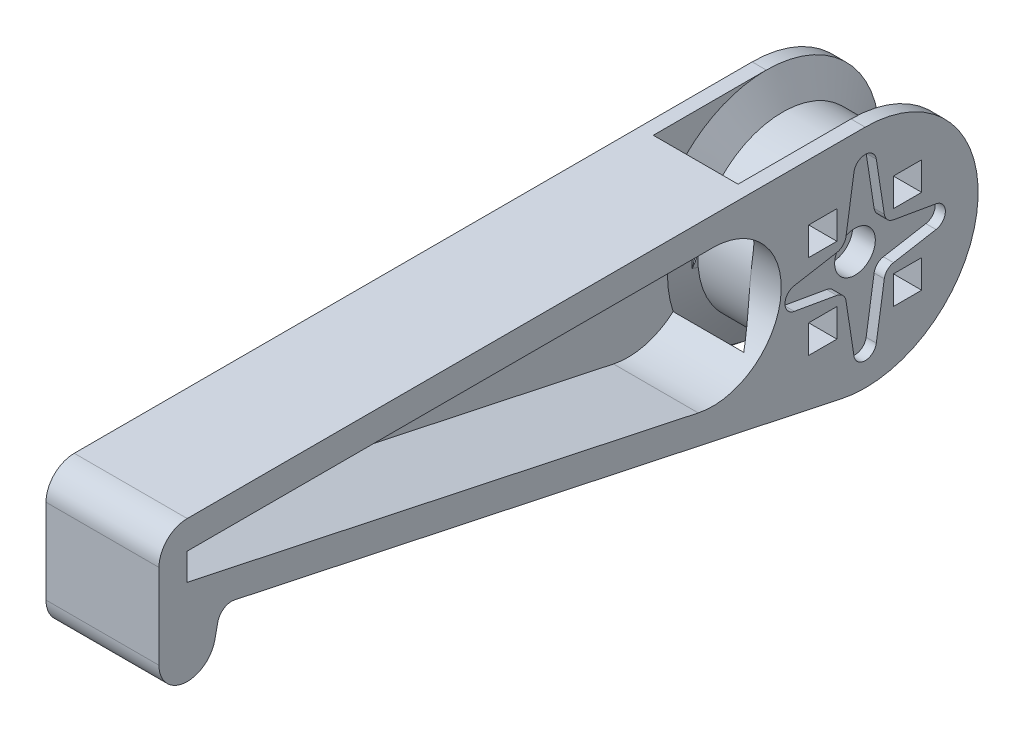
SolidWorks part; units mm, degrees
ref_plane "Front Plane" through (0, 0, 0) normal (0, 0, 1) x (1, 0, 0)
ref_plane "Top Plane" through (0, 0, 0) normal (0, 1, 0) x (1, 0, 0)
ref_plane "Right Plane" through (0, 0, 0) normal (1, 0, 0) x (0, 0, -1)
sketch "Sketch1" plane through (0, 0, 0) normal (1, 0, 0) x (0, 0, -1)
  line L0 (-141.7611, 4.2263) -> (-5.2917, -24.8427)
  line L1 (-146.1893, -1.3229) -> (-145.5279, 1.7824)
  line L2 (0, 25.4) -> (-152.4, 25.4)
  line L3 (-158.75, 19.05) -> (-158.75, 0)
  arc A0 (-5.2917, -24.8427) -> (0, 25.4) centre (0, 0) ccw
  arc A1 (-158.75, 0) -> (-146.1893, -1.3229) centre (-152.4, 0) ccw
  arc A2 (-152.4, 25.4) -> (-158.75, 19.05) centre (-152.4, 19.05) ccw
  arc A3 (-141.7611, 4.2263) -> (-145.5279, 1.7824) centre (-142.4225, 1.121) ccw
  dimension "D1" = 50.8
  dimension "D3" = 152.4
  dimension "D4" = 6.35
  dimension "D2" = 12.7
  dimension "D5" = 3.175
extrude "Boss-Extrude1" add sketch "Sketch1" along normal blind 25.4 contours L2 A2 L3 A1 L1 A3 L0 A0
sketch "Sketch2" plane through (25.4, 0, 0) normal (1, 0, 0) x (0, 0, -1)
  line L4 (-140.4382, 10.437) -> (-152.4, 12.9849)
  line L8 (0, 19.05) -> (-152.4, 19.05)
  line L9 (-152.4, 19.05) -> (-152.4, 0)
  line L10 (-152.4, 0) -> (-151.7385, 3.1053)
  line L11 (-140.4382, 10.437) -> (-3.9688, -18.632)
  line L12 (-34.298, 19.05) -> (-152.4, 19.05)
  line L13 (-152.4, 19.05) -> (-152.4, 12.9849)
  line L15 (-140.4382, 10.437) -> (-37.5141, -11.4866)
  arc A4 (-3.9688, -18.632) -> (0, 19.05) centre (0, 0) ccw construction
  arc A5 (-37.5141, -11.4866) -> (-34.298, 19.05) centre (-34.298, 3.6123) ccw
  arc A8 (-3.9688, -18.632) -> (0, 19.05) centre (0, 0) ccw
  arc A9 (-140.4382, 10.437) -> (-151.7385, 3.1053) centre (-142.4225, 1.121) ccw
  arc A10 (-3.9688, -18.632) -> (0, 19.05) centre (0, 0) ccw construction
  dimension "D1" = 6.35
extrude "Cut-Extrude2" cut sketch "Sketch2" against normal blind 19.05
sketch "Sketch4" plane through (25.4, 0, 0) normal (1, 0, 0) x (0, 0, -1)
  point P36 (4.5777, -4.486)
  point P39 (-4.5777, -4.486)
  point P42 (-4.5777, 4.486)
  point P45 (4.5777, 4.486)
  line B0 (0, -1000) -> (0, 49000) construction
  line B1 (-1000, 0) -> (49000, 0) construction
  line B2 (0, 20.066) -> (-50000, 20.066) construction
  line B3 (18.034, 0) -> (18.034, 50000) construction
  line B4 (0, -20.066) -> (50000, -20.066) construction
  line B5 (-18.034, 0) -> (-18.034, 50000) construction
  line B6 (15.9312, -2.5021) -> (6.3735, -4.1722)
  line B7 (-15.9312, 2.5021) -> (-6.3735, 4.1722)
  line B8 (-2.5104, 17.9125) -> (-4.3002, 6.2878)
  line B9 (2.5104, -17.9125) -> (4.3002, -6.2878)
  line B10 (-2.5104, -17.9125) -> (-4.3002, -6.2878)
  line B11 (-15.9312, -2.5021) -> (-6.3735, -4.1722)
  line B12 (2.5104, 17.9125) -> (4.3002, 6.2878)
  line B13 (15.9312, 2.5021) -> (6.3735, 4.1722)
  arc B14 (2.5104, 17.9125) -> (-2.5104, 17.9125) centre (0, 17.526) ccw
  arc B15 (15.9312, -2.5021) -> (15.9312, 2.5021) centre (15.494, 0) ccw
  arc B16 (-2.5104, -17.9125) -> (2.5104, -17.9125) centre (0, -17.526) ccw
  arc B17 (-15.9312, 2.5021) -> (-15.9312, -2.5021) centre (-15.494, 0) ccw
  arc B18 (6.3735, -4.1722) -> (4.3002, -6.2878) centre (6.8107, -6.6743) ccw
  arc B19 (-4.3002, -6.2878) -> (-6.3735, -4.1722) centre (-6.8107, -6.6743) ccw
  arc B20 (-6.3735, 4.1722) -> (-4.3002, 6.2878) centre (-6.8107, 6.6743) ccw
  arc B21 (4.3002, 6.2878) -> (6.3735, 4.1722) centre (6.8107, 6.6743) ccw
sketch_block_instance "Block1-1"
sketch_block "Block1" parameters "D1"=5.08, "D6"=2.54, "D2"=40.132, "D3"=36.068, "D4"=10.414, "D5"=10.414
extrude "Cut-Extrude3" cut sketch "Sketch4" against normal blind 2.286
sketch "Sketch5" plane through (23.114, 0, 0) normal (1, 0, 0) x (0, 0, -1)
  circle A0 centre (0, 0) radius 4.572
  dimension "D1" = 9.144
extrude "Cut-Extrude4" cut sketch "Sketch5" against normal blind 5.08
sketch "Sketch6" plane through (0, 0, 0) normal (0, 0, 1) x (1, 0, 0)
  line L8 (25.4, 25.4) -> (0, 25.4)
  line L9 (25.4, -25.4) -> (0, -25.4)
  line L11 (22.225, 25.4) -> (3.175, 25.4)
  line L12 (3.175, 25.4) -> (6.8412, 19.05)
  line L13 (6.8412, 19.05) -> (18.5588, 19.05)
  line L14 (18.5588, 19.05) -> (22.225, 25.4)
  line L15 (12.7, -974.6) -> (12.7, 49025.4) construction
  line L16 (25.4, 6.2878) -> (25.4, 17.9125) construction
  line L17 (0, 25.4) -> (0, -25.4) construction
  line L18 (25.4, 6.2878) -> (25.4, 17.9125) construction
  line L19 (0, 25.4) -> (0, -25.4) construction
  line L20 (-1000, 0) -> (49000, 0) construction
  point P11 (12.7, 25.4)
  dimension "D1" = 19.05
  dimension "D2" = 120
  dimension "D3" = 6.35
revolve "Cut-Revolve1" cut sketch "Sketch6" angle 360 about L20
ref_plane "Plane1" through (0, 0, 21.9183) normal (0, 0, 1) x (1, 0, 0)
sketch "Sketch8" plane through (0, 0, 0) normal (0, 0, 1) x (1, 0, 0)
  line L0 (3.175, 25.4) -> (6.8412, 19.05) construction
  line L2 (6.8412, 19.05) -> (18.5588, 19.05) construction
  line L3 (18.5588, 19.05) -> (22.225, 25.4) construction
  line L4 (3.175, 25.4) -> (6.8412, 19.05)
  line L5 (3.175, 25.4) -> (3.175, 50.8)
  line L6 (6.8412, 19.05) -> (18.5588, 19.05)
  line L7 (18.5588, 19.05) -> (22.225, 25.4)
  line L8 (3.175, 50.8) -> (22.225, 50.8)
  line L9 (22.225, 50.8) -> (22.225, 25.4)
  dimension "D1" = 25.4
revolve "Cut-Revolve2" cut sketch "Sketch8" angle 45 about L20
mirror "Mirror1" about plane through (0, 0, 0) normal (0, 1, 0) of "Cut-Revolve2"
sketch "Sketch9" plane through (25.4, 0, 0) normal (1, 0, 0) x (0, 0, -1)
  line L0 (-1000, 0) -> (49000, 0) construction
  line L1 (0, -1000) -> (0, 49000) construction
  line L2 (12.7, 6.35) -> (6.35, 6.35)
  line L3 (-12.7, 6.35) -> (-6.35, 6.35)
  line L4 (-12.7, 6.35) -> (-12.7, 12.7)
  line L5 (-12.7, 12.7) -> (-6.35, 12.7)
  line L6 (-6.35, 6.35) -> (-6.35, 12.7)
  line L7 (-12.7, 6.35) -> (-6.35, 12.7) construction
  line L8 (-12.7, 12.7) -> (-6.35, 6.35) construction
  line L9 (12.7, 6.35) -> (12.7, 12.7)
  line L10 (12.7, 12.7) -> (6.35, 12.7)
  line L11 (6.35, 6.35) -> (6.35, 12.7)
  line L12 (12.7, -6.35) -> (6.35, -6.35)
  line L13 (12.7, -6.35) -> (12.7, -12.7)
  line L14 (12.7, -12.7) -> (6.35, -12.7)
  line L15 (6.35, -6.35) -> (6.35, -12.7)
  line L16 (-12.7, -12.7) -> (-6.35, -12.7)
  line L17 (-6.35, -6.35) -> (-6.35, -12.7)
  line L18 (-12.7, -6.35) -> (-6.35, -6.35)
  line L19 (-12.7, -6.35) -> (-12.7, -12.7)
  circle A0 centre (-9.525, 9.525) radius 3.175 construction
  circle A1 centre (9.525, 9.525) radius 3.175 construction
  circle A2 centre (9.525, -9.525) radius 3.175 construction
  circle A3 centre (-9.525, -9.525) radius 3.175 construction
  dimension "D1" = 9.525
  dimension "D3" = 6.35
  dimension "D2" = 9.525
extrude "Cut-Extrude5" cut sketch "Sketch9" against normal offset from surface (22.225 mm away) 3.175 up to face at (0, 5.3995, 110.3976)
equation "\"D5@Block1\"=\"D4@Block1\""
equation "\"D2@Sketch9\"=\"D1@Sketch9\""
